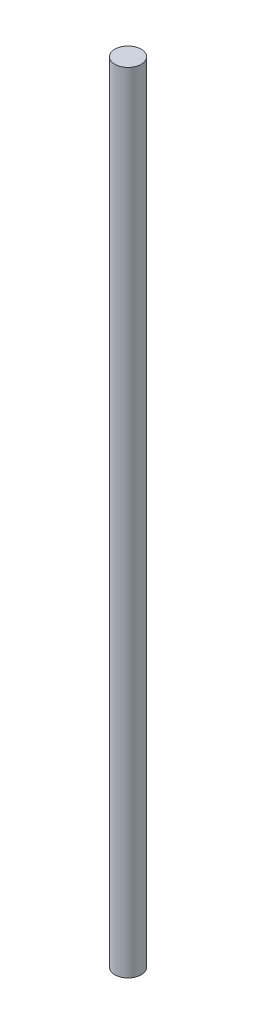
SolidWorks part; units mm, degrees
ref_plane "Alzado" through (0, 0, 0) normal (0, 0, 1) x (1, 0, 0)
ref_plane "Planta" through (0, 0, 0) normal (0, 1, 0) x (1, 0, 0)
ref_plane "Vista lateral" through (0, 0, 0) normal (1, 0, 0) x (0, 0, -1)
sketch "Croquis1" plane through (0, 0, 0) normal (0, 1, 0) x (1, 0, 0)
  circle A0 centre (0, 0) radius 1.5
  dimension "D1" = 3
extrude "Saliente-Extruir1" add sketch "Croquis1" along normal blind 90
